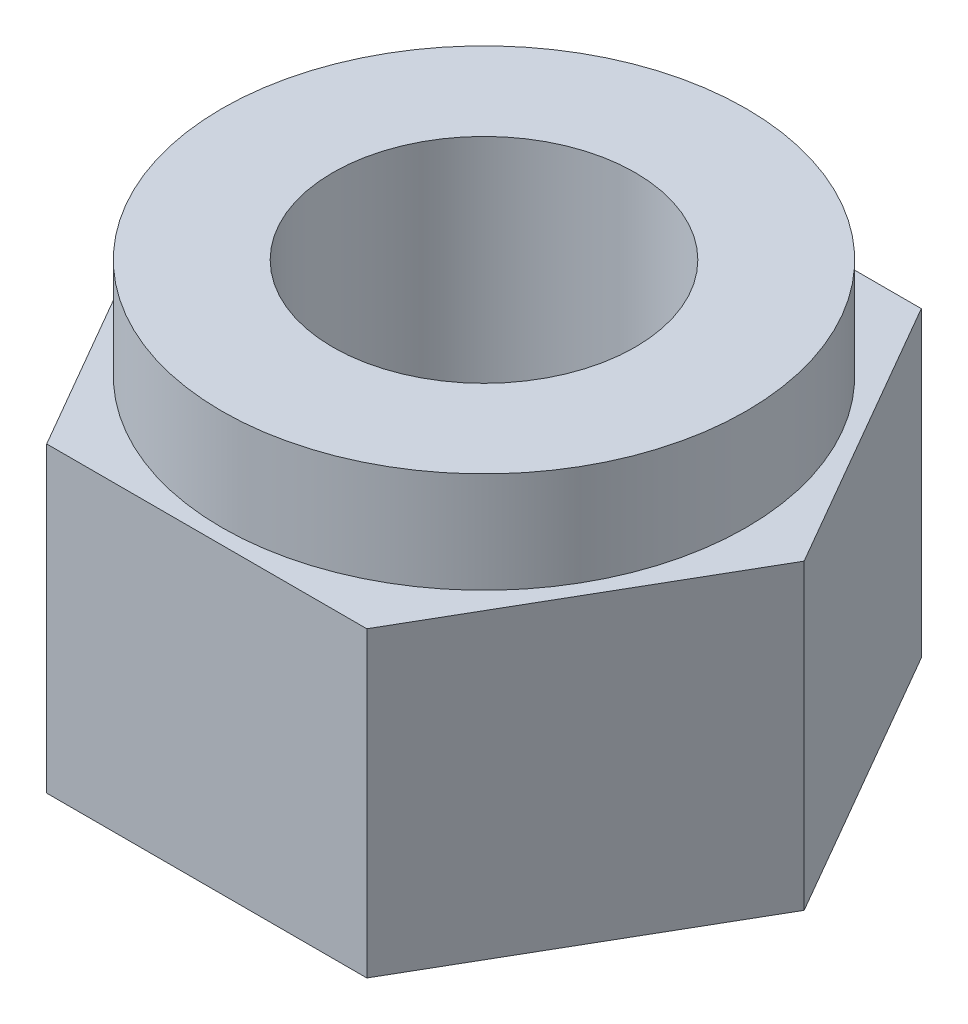
SolidWorks part; units mm, degrees
material "AISI 304"
ref_plane "Plan de face" through (0, 0, 0) normal (0, 0, 1) x (1, 0, 0)
ref_plane "Plan de dessus" through (0, 0, 0) normal (0, 1, 0) x (1, 0, 0)
ref_plane "Plan de droite" through (0, 0, 0) normal (1, 0, 0) x (0, 0, -1)
sketch "Esquisse1" plane through (0, 0, 0) normal (0, 1, 0) x (1, 0, 0)
  line L1 (3.1754, 0) -> (1.5877, 2.75)
  line L2 (1.5877, 2.75) -> (-1.5877, 2.75)
  line L3 (-1.5877, 2.75) -> (-3.1754, 0)
  line L4 (-3.1754, 0) -> (-1.5877, -2.75)
  line L5 (-1.5877, -2.75) -> (1.5877, -2.75)
  line L6 (1.5877, -2.75) -> (3.1754, 0)
  circle A0 centre (0, 0) radius 3.1754 construction
  dimension "D1" = 6.3509
  dimension "D2" = 3.1754
extrude "Boss.-Extru.1" add sketch "Esquisse1" along normal blind 3
sketch "Esquisse2" plane through (0, 0, 0) normal (0, 1, 0) x (1, 0, 0)
  circle A0 centre (0, 0) radius 2.6
  circle A1 centre (0, 0) radius 1.5
  dimension "D1" = 5.2
  dimension "D2" = 3
extrude "Boss.-Extru.2" add sketch "Esquisse2" along normal blind 1 from offset 3
sketch "Esquisse3" plane through (0, 0, 0) normal (0, 1, 0) x (1, 0, 0)
  circle A0 centre (0, 0) radius 1.5
  dimension "D1" = 3
extrude "Enlèv. mat.-Extru.1" cut sketch "Esquisse3" along normal through all
